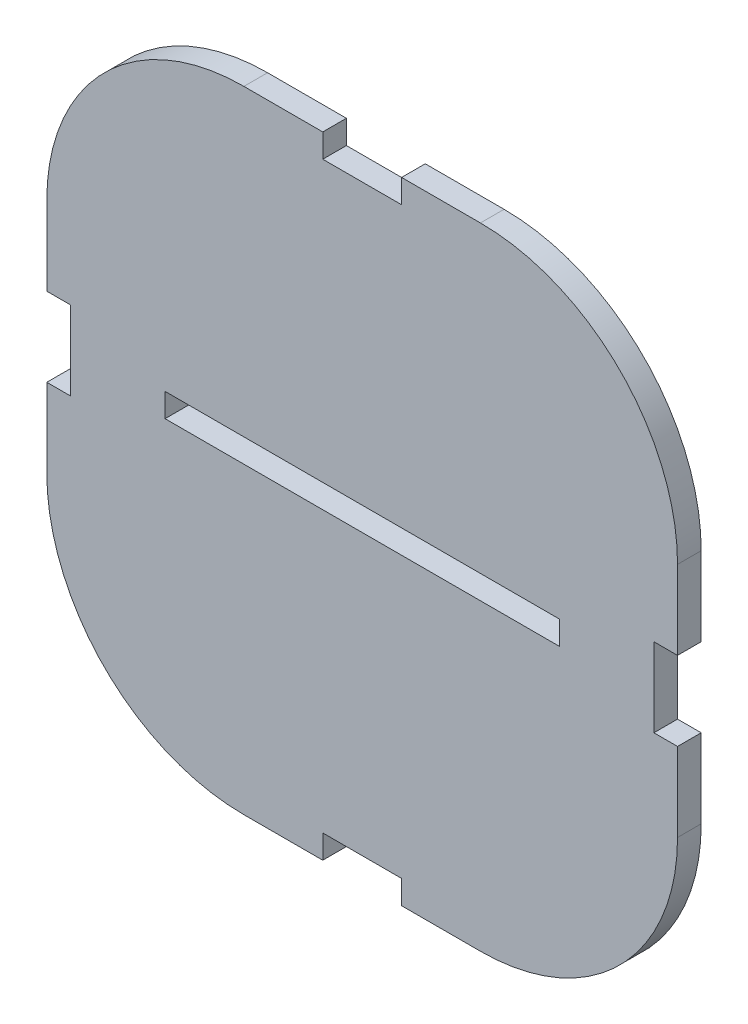
SolidWorks part; units mm, degrees
ref_plane "前基準面" through (0, 0, 0) normal (0, 0, 1) x (1, 0, 0)
ref_plane "上基準面" through (0, 0, 0) normal (0, 1, 0) x (1, 0, 0)
ref_plane "右基準面" through (0, 0, 0) normal (1, 0, 0) x (0, 0, -1)
sketch "草圖1" plane through (0, 0, 0) normal (0, 0, 1) x (1, 0, 0)
  line L0 (-40, 0) -> (40, 0) construction
  line L1 (-15, 40) -> (15, 40)
  line L2 (-40, 15) -> (-40, -15)
  line L3 (-15, -40) -> (15, -40)
  line L4 (40, 15) -> (40, -15)
  line L5 (-40, 40) -> (40, -40) construction
  line L6 (-40, -40) -> (40, 40) construction
  line L7 (0, 40) -> (0, -40) construction
  line L8 (-5, -37) -> (5, -37)
  line L9 (-40, -5) -> (-37, -5)
  line L10 (-40, -5) -> (-40, 5)
  line L11 (-40, 5) -> (-37, 5)
  line L12 (-37, -5) -> (-37, 5)
  line L13 (-5, 40) -> (5, 40)
  line L14 (-5, 40) -> (-5, 37)
  line L15 (-5, 37) -> (5, 37)
  line L16 (5, 40) -> (5, 37)
  line L17 (5, -40) -> (5, -37)
  line L18 (-5, -40) -> (5, -40)
  line L19 (-5, -40) -> (-5, -37)
  line L20 (40, 5) -> (37, 5)
  line L21 (37, -5) -> (37, 5)
  line L22 (40, -5) -> (37, -5)
  line L23 (40, -5) -> (40, 5)
  line L25 (-25, 1.5) -> (25, 1.5)
  line L26 (-25, 1.5) -> (-25, -1.5)
  line L27 (-25, -1.5) -> (25, -1.5)
  line L28 (25, 1.5) -> (25, -1.5)
  line L29 (-25, 1.5) -> (25, -1.5) construction
  line L30 (-25, -1.5) -> (25, 1.5) construction
  arc A0 (15, 40) -> (40, 15) centre (15, 15) cw
  arc A1 (15, -40) -> (40, -15) centre (15, -15) ccw
  arc A2 (-40, -15) -> (-15, -40) centre (-15, -15) ccw
  arc A3 (-15, 40) -> (-40, 15) centre (-15, 15) ccw
  point P0 (0, 0)
  point P26 (-37, 0)
  point P27 (0, 37)
  point P32 (0, 0)
  dimension "D3" = 25
  dimension "D1" = 80
  dimension "D2" = 80
  dimension "D4" = 3
  dimension "D5" = 10
  dimension "D6" = 3
  dimension "D7" = 10
  dimension "D8" = 3
  dimension "D9" = 50
extrude "填料-伸長1" add sketch "草圖1" along normal blind 3 contours L1 A3 L2 L11 L12 L9 A2 L3 L19 L8 L17 A1 L4 L22 L21 L20 A0 L16 L15 L14 L25 L28 L27 L26
